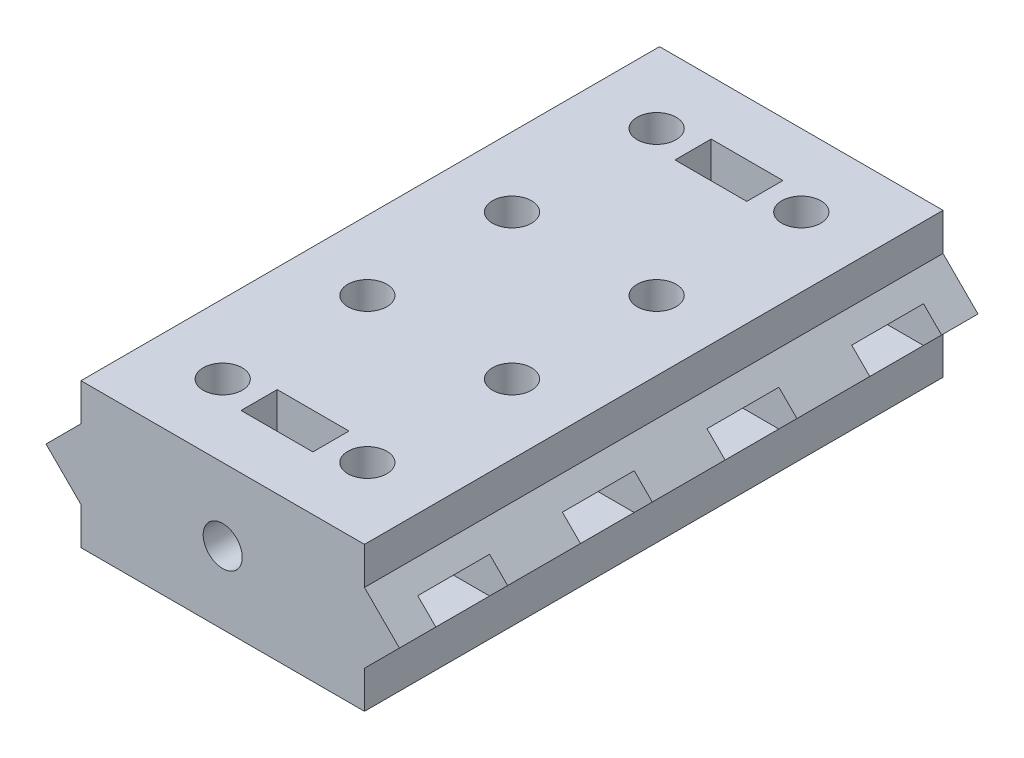
SolidWorks part; units mm, degrees
ref_plane "Front Plane" through (0, 0, 0) normal (0, 0, 1) x (1, 0, 0)
ref_plane "Top Plane" through (0, 0, 0) normal (0, 1, 0) x (1, 0, 0)
ref_plane "Right Plane" through (0, 0, 0) normal (1, 0, 0) x (0, 0, -1)
sketch "Sketch1" plane through (0, 0, 0) normal (0, 0, 1) x (1, 0, 0)
  line L1 (-25.4, 6.35) -> (-25.4, 12.7)
  line L2 (-25.4, 12.7) -> (25.4, 12.7)
  line L3 (25.4, 12.7) -> (25.4, 6.35)
  line L7 (25.4, -6.35) -> (25.4, -12.7)
  line L8 (25.4, -12.7) -> (-25.4, -12.7)
  line L9 (-25.4, -12.7) -> (-25.4, -6.35)
  line L13 (0, 0) -> (0, 12.7) construction
  line L14 (0, 0) -> (0, -12.7) construction
  line L15 (-25.4, 6.35) -> (-31.75, 0)
  line L16 (-31.75, 0) -> (-25.4, -6.35)
  line L17 (25.4, 6.35) -> (31.75, 0)
  line L18 (31.75, 0) -> (25.4, -6.35)
  point P18 (0, 12.7)
  point P19 (0, -12.7)
  dimension "D1" = 25.4
  dimension "D2" = 6.35
  dimension "D3" = 6.35
  dimension "D5" = 50.8
  dimension "D6" = 6.35
extrude "Boss-Extrude1" add sketch "Sketch1" along normal mid plane 101.6
sketch "Sketch2" plane through (0, 0, 0) normal (0, 1, 0) x (1, 0, 0)
  line L0 (48.874, 6.3942) -> (12.7, 6.3942)
  line L1 (7.239, 9.5471) -> (12.7, 6.3942)
  line L2 (7.239, 15.8529) -> (7.239, 9.5471)
  line L3 (12.7, 19.0058) -> (7.239, 15.8529)
  line L4 (12.7, 19.0058) -> (48.874, 19.0058)
  line L5 (48.874, 19.0058) -> (48.874, 6.3942)
  line L6 (48.874, -19.0058) -> (12.7, -19.0058)
  line L7 (7.239, -15.8529) -> (12.7, -19.0058)
  line L8 (7.239, -9.5471) -> (7.239, -15.8529)
  line L9 (25.4, 50.8) -> (-25.4, 50.8) construction
  line L10 (25.4, -50.8) -> (25.4, 50.8) construction
  line L11 (7.239, 34.9471) -> (12.7, 31.7942)
  line L12 (12.7, 31.7942) -> (18.161, 34.9471) construction
  line L13 (18.161, 34.9471) -> (18.161, 41.2529) construction
  line L14 (18.161, 41.2529) -> (12.7, 44.4058) construction
  line L15 (12.7, 44.4058) -> (7.239, 41.2529)
  line L16 (7.239, 41.2529) -> (7.239, 34.9471)
  line L17 (12.7, 44.4058) -> (48.874, 44.4058)
  line L18 (48.874, 44.4058) -> (48.874, 31.7942)
  line L19 (48.874, 31.7942) -> (12.7, 31.7942)
  line L20 (12.7, -6.3942) -> (7.239, -9.5471)
  line L21 (12.7, -6.3942) -> (48.874, -6.3942)
  line L22 (48.874, -6.3942) -> (48.874, -19.0058)
  line L23 (48.874, -44.4058) -> (12.7, -44.4058)
  line L24 (7.239, -41.2529) -> (12.7, -44.4058)
  line L25 (7.239, -34.9471) -> (7.239, -41.2529)
  line L26 (12.7, -31.7942) -> (7.239, -34.9471)
  line L27 (12.7, -31.7942) -> (48.874, -31.7942)
  line L28 (48.874, -31.7942) -> (48.874, -44.4058)
  line L29 (0, 0) -> (0, 15.8529) construction
  line L30 (-7.239, -34.9471) -> (-7.239, -41.2529)
  line L31 (-18.161, 41.2529) -> (-12.7, 44.4058) construction
  line L32 (-18.161, 34.9471) -> (-18.161, 41.2529) construction
  line L33 (-12.7, 31.7942) -> (-18.161, 34.9471) construction
  line L34 (-48.874, -31.7942) -> (-48.874, -44.4058)
  line L35 (-12.7, -31.7942) -> (-48.874, -31.7942)
  line L36 (-12.7, -31.7942) -> (-7.239, -34.9471)
  line L37 (-7.239, -41.2529) -> (-12.7, -44.4058)
  line L38 (-48.874, -44.4058) -> (-12.7, -44.4058)
  line L39 (-48.874, -6.3942) -> (-48.874, -19.0058)
  line L40 (-12.7, -6.3942) -> (-48.874, -6.3942)
  line L41 (-12.7, -6.3942) -> (-7.239, -9.5471)
  line L42 (-48.874, 31.7942) -> (-12.7, 31.7942)
  line L43 (-48.874, 44.4058) -> (-48.874, 31.7942)
  line L44 (-12.7, 44.4058) -> (-48.874, 44.4058)
  line L45 (-7.239, 41.2529) -> (-7.239, 34.9471)
  line L46 (-12.7, 44.4058) -> (-7.239, 41.2529)
  line L47 (-7.239, 34.9471) -> (-12.7, 31.7942)
  line L48 (-7.239, -9.5471) -> (-7.239, -15.8529)
  line L49 (-7.239, -15.8529) -> (-12.7, -19.0058)
  line L50 (-48.874, -19.0058) -> (-12.7, -19.0058)
  line L51 (-48.874, 19.0058) -> (-48.874, 6.3942)
  line L52 (-12.7, 19.0058) -> (-48.874, 19.0058)
  line L53 (-12.7, 19.0058) -> (-7.239, 15.8529)
  line L54 (-7.239, 15.8529) -> (-7.239, 9.5471)
  line L55 (-7.239, 9.5471) -> (-12.7, 6.3942)
  line L56 (-48.874, 6.3942) -> (-12.7, 6.3942)
  line L57 (-31.75, -50.8) -> (-31.75, 50.8) construction
  circle A0 centre (-12.7, 38.1) radius 5.461 construction
  circle A1 centre (12.7, 38.1) radius 5.461 construction
  dimension "D1" = 4
  dimension "D3" = 10.922
  dimension "D4" = 12.7
  dimension "D6" = 12.7
extrude "Cut-Extrude1" cut sketch "Sketch2" against normal mid plane 6.35
sketch "Sketch3" plane through (0, 12.7, 0) normal (0, 1, 0) x (1, 0, 0)
  line L0 (25.4, 50.8) -> (-25.4, 50.8) construction
  circle A0 centre (-12.7, 38.1) radius 3.429
  circle A1 centre (12.7, 38.1) radius 3.429
  circle A2 centre (12.7, 12.7) radius 3.429
  circle A3 centre (-12.7, 12.7) radius 3.429
  circle A4 centre (-12.7, -12.7) radius 3.429
  circle A5 centre (12.7, -12.7) radius 3.429
  circle A6 centre (-12.7, -38.1) radius 3.429
  circle A7 centre (12.7, -38.1) radius 3.429
  dimension "D1" = 6.858
  dimension "D2" = 12.7
  dimension "D3" = 12.7
  dimension "D4" = 4
extrude "Cut-Extrude2" cut sketch "Sketch3" against normal through all
sketch "Sketch5" plane through (0, 0, 50.8) normal (0, 0, 1) x (1, 0, 0)
  circle A0 centre (0, 0) radius 3.429
  dimension "D1" = 6.858
extrude "Cut-Extrude4" cut sketch "Sketch5" against normal through all
sketch "Sketch10" plane through (0, 0, 0) normal (0, 0, 1) x (1, 0, 0)
  line L0 (25.4, 12.7) -> (-25.4, 12.7) construction
  line L1 (3.1529, -5.461) -> (6.3058, 0)
  line L2 (6.3058, 0) -> (3.1529, 5.461) construction
  line L3 (3.1529, 5.461) -> (-3.1529, 5.461) construction
  line L4 (-3.1529, 5.461) -> (-6.3058, 0) construction
  line L5 (-6.3058, 0) -> (-3.1529, -5.461)
  line L6 (-3.1529, -5.461) -> (3.1529, -5.461)
  line L7 (6.3058, 0) -> (6.3058, 55.1662)
  line L8 (6.3058, 55.1662) -> (-6.3058, 55.1662)
  line L9 (-6.3058, 55.1662) -> (-6.3058, 0)
  circle A0 centre (0, 0) radius 5.461 construction
  dimension "D1" = 10.922
extrude "Cut-Extrude9" cut sketch "Sketch10" against normal mid plane 6.35 from offset 38.1
mirror "Mirror1" about plane through (0, 0, 0) normal (0, 0, 1) of "Cut-Extrude9"
sketch "Sketch11" plane through (0, 0, 50.8) normal (0, 0, 1) x (1, 0, 0)
  line L0 (-24.892, 12.7) -> (-24.892, 6.1396)
  line L1 (25.4, 12.7) -> (-25.4, 12.7) construction
  line L2 (-24.892, 6.1396) -> (-31.0316, 0)
  line L3 (-31.0316, 0) -> (-24.892, -6.1396)
  line L4 (-24.892, -6.1396) -> (-24.892, -12.7)
  line L5 (-25.4, -12.7) -> (25.4, -12.7) construction
  line L6 (-24.892, 12.7) -> (24.892, 12.7)
  line L7 (-24.892, -12.7) -> (24.892, -12.7)
  line L8 (0, 12.7) -> (0, -12.7) construction
  line L9 (-25.4, -9.525) -> (-24.892, -9.525) construction
  line L10 (-25.4, -6.35) -> (-25.4, -12.7) construction
  line L11 (-28.321, -3.429) -> (-27.9618, -3.0698) construction
  line L12 (-31.75, 0) -> (-25.4, -6.35) construction
  line L13 (28.321, -3.429) -> (27.9618, -3.0698) construction
  line L14 (25.4, -9.525) -> (24.892, -9.525) construction
  line L15 (24.892, -6.1396) -> (24.892, -12.7)
  line L16 (31.0316, 0) -> (24.892, -6.1396)
  line L17 (24.892, 6.1396) -> (31.0316, 0)
  line L18 (24.892, 12.7) -> (24.892, 6.1396)
  dimension "D1" = 0.508
extrude "Trim" cut sketch "Sketch11" against normal through all flip side to cut
